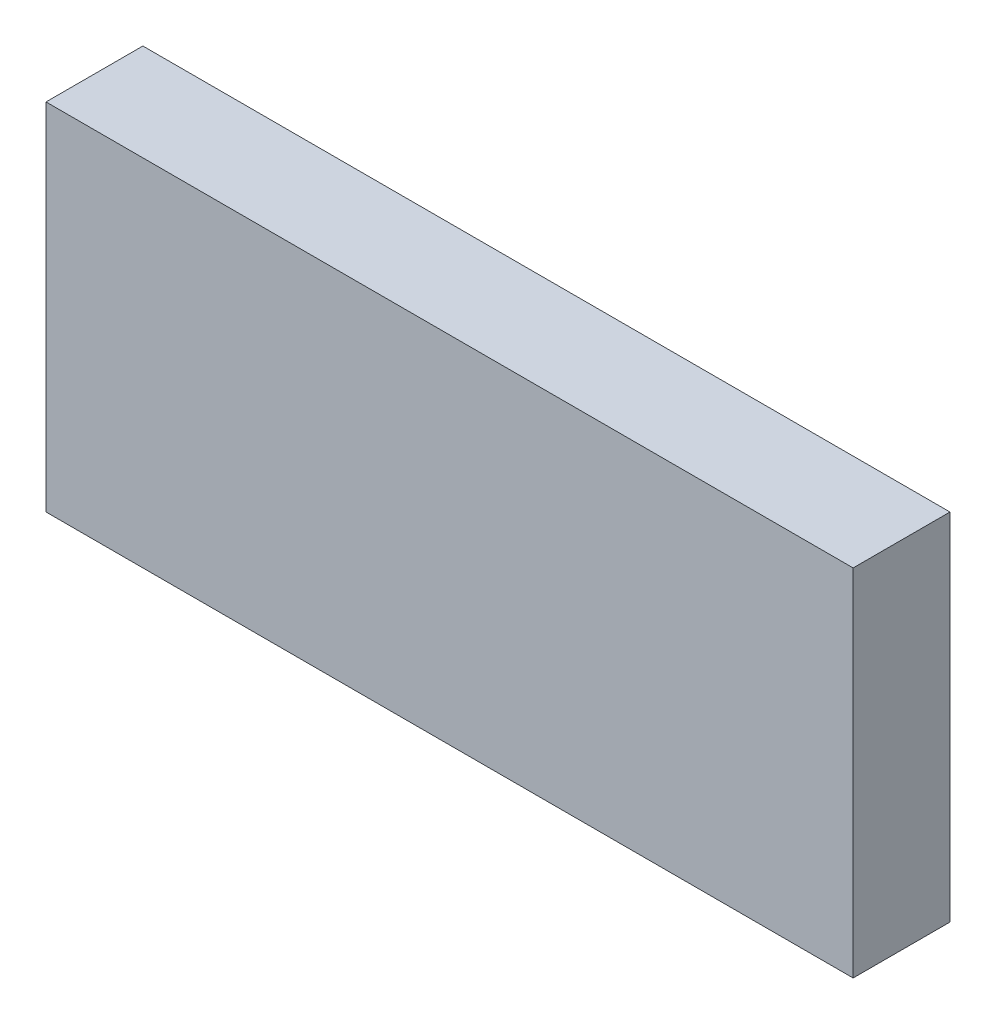
SolidWorks part; units mm, degrees
ref_plane "Plan de face" through (0, 0, 0) normal (0, 0, 1) x (1, 0, 0)
ref_plane "Plan de dessus" through (0, 0, 0) normal (0, 1, 0) x (1, 0, 0)
ref_plane "Plan de droite" through (0, 0, 0) normal (1, 0, 0) x (0, 0, -1)
sketch "Esquisse1" plane through (0, 0, 0) normal (0, 0, 1) x (1, 0, 0)
  line L1 (0, 0) -> (-50, 0)
  line L2 (0, 0) -> (0, 22)
  line L3 (0, 22) -> (-50, 22)
  line L4 (-50, 0) -> (-50, 22)
  dimension "D1" = 22
  dimension "D2" = 50
extrude "Boss.-Extru.1" add sketch "Esquisse1" along normal blind 6
